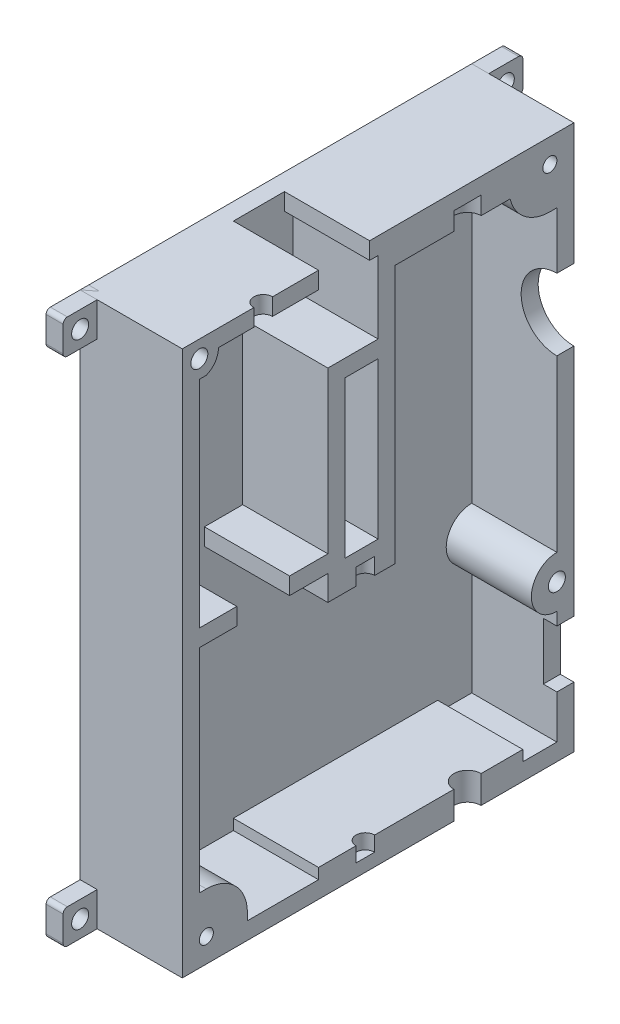
SolidWorks part; units mm, degrees
ref_plane "前视基准面" through (0, 0, 0) normal (0, 0, 1) x (1, 0, 0)
ref_plane "上视基准面" through (0, 0, 0) normal (0, 1, 0) x (1, 0, 0)
ref_plane "右视基准面" through (0, 0, 0) normal (1, 0, 0) x (0, 0, -1)
other "Configuration Table"
sketch "草图1" plane through (0, 0, 0) normal (1, 0, 0) x (0, 0, -1)
  line L1 (-23, 32) -> (23, 32)
  line L2 (-23, 32) -> (-23, -32)
  line L3 (-23, -32) -> (23, -32)
  line L4 (23, 32) -> (23, -32)
  line L5 (-23, 32) -> (23, -32) construction
  line L6 (-23, -32) -> (23, 32) construction
  point P0 (0, 0)
  dimension "D1" = 64
  dimension "D2" = 46
extrude "凸台-拉伸1" add sketch "草图1" along normal blind 12
shell "抽壳1" thickness 2
sketch "草图3" plane through (2, 0, 0) normal (1, 0, 0) x (0, 0, -1)
  line L3 (-6, 23.2) -> (-6, 2.7) construction
  line L10 (-21, 2.7) -> (-6, 2.7) construction
  line L13 (-16.5, 2.7) -> (-16.5, 1.2) construction
  line L14 (-10.5, 1.2) -> (-10.5, 2.7) construction
  line L18 (2.5, -2.55) -> (-5.5, -2.55) construction
  line L19 (-5.9, 21.5) -> (0, 21.5)
  line L20 (-5.9, 21.5) -> (-5.9, 2.6)
  line L21 (-5.9, -2.35) -> (2, -2.35)
  line L22 (2, 17.175) -> (2, -2.35)
  line L25 (8, 24.825) -> (8, -27.175) construction
  line L26 (21, 30) -> (-21, 30) construction
  line L27 (-21, 30) -> (-21, -30) construction
  line L28 (0, 30) -> (2, 30)
  line L29 (0, 30) -> (0, 21.5)
  line L31 (2, 30) -> (2, 17.175)
  line L32 (-3.9, 19.5) -> (0, 19.5)
  line L33 (-3.9, 19.5) -> (-3.9, 1.15)
  line L34 (-3.9, 1.15) -> (0, 1.15)
  line L35 (0, 19.5) -> (0, 1.15)
  line L36 (-21, 2.6) -> (-16.6, 2.6)
  line L37 (-21, 2.6) -> (-21, 0.6)
  line L38 (-21, 0.6) -> (-16.6, 0.6)
  line L39 (-16.6, 2.6) -> (-16.6, 0.6)
  line L41 (-10.4, 2.6) -> (-5.9, 2.6)
  line L42 (-10.4, 2.6) -> (-10.4, 0.6)
  line L43 (-10.4, 0.6) -> (-5.9, 0.6)
  line L48 (-5.9, 0.6) -> (-5.9, -2.35)
  dimension "D2" = 0.2
  dimension "D3" = 6
  dimension "D4" = 8.5
  dimension "D5" = 2
  dimension "D6" = 2
  dimension "D7" = 3.5
  dimension "D8" = 2
  dimension "D9" = 2
  dimension "D10" = 0.1
  dimension "D11" = 0.1
  dimension "D12" = 0.1
  dimension "D13" = 2
  dimension "D14" = 2
  dimension "D15" = 0.1
extrude "机位凸台-拉伸6" add sketch "草图3" along normal up to surface (10 mm away) up to face at (12, 0, 0)
sketch "草图9" plane through (2, 0, 0) normal (1, 0, 0) x (0, 0, -1)
  line L0 (-21, -30) -> (21, -30) construction
  line L1 (-7, -28.75) -> (17, -28.75)
  line L2 (-7, -28.75) -> (-7, -30)
  line L3 (-7, -30) -> (17, -30)
  line L4 (17, -28.75) -> (17, -30)
  line L5 (0.2682, -28.55) -> (1.3325, -28.55) construction
  line L6 (21, -30) -> (21, 30) construction
  dimension "D1" = 0.2
  dimension "D2" = 24
  dimension "D3" = 4
extrude "杆位凸台-拉伸9" add sketch "草图9" along normal up to surface (10 mm away) up to face at (12, 6.1722, 6.4222)
sketch "草图16" plane through (2, 0, 0) normal (1, 0, 0) x (0, 0, -1)
  line L0 (2, 28) -> (21, 28)
  line L1 (2, -2.35) -> (2, 30) construction
  line L2 (21, -30) -> (21, 30) construction
  line L3 (21, 30) -> (2, 30) construction
  line L4 (21, 30) -> (2, 30)
  line L5 (21, 30) -> (21, 28)
  line L6 (2, 28) -> (2, 30)
  dimension "D1" = 2
extrude "凸台-拉伸9" add sketch "草图16" along normal up to surface (10 mm away) up to face at (12, -0.2909, 4.3455)
sketch "草图17" plane through (0, 32, 0) normal (0, 1, 0) x (1, 0, 0)
  circle A1 centre (12, 10.5) radius 1.6
  circle A2 centre (12, 10.5) radius 1.5 construction
  dimension "D1" = 0.1
extrude "后部孔位3切除-拉伸3" cut sketch "草图17" along normal offset from surface (2.1 mm away) 1.9 from surface at -4 up to face at (6, 32, 0) starting at face at (7, 28, -11.5)
sketch "草图4" plane through (0, 32, 0) normal (0, 1, 0) x (1, 0, 0)
  line L1 (12, -1) -> (2, -1)
  line L2 (12, -1) -> (12, -7)
  line L3 (12, -7) -> (2, -7)
  line L4 (2, -1) -> (2, -7)
  line L7 (12, -21) -> (2, -21) construction
  line L8 (2, 0) -> (2, -21) construction
  circle A1 centre (12, -13.5) radius 1.1
  circle A5 centre (12, -13.5) radius 1 construction
  dimension "D1" = 0.1
  dimension "D3" = 14
  dimension "D4" = 6
extrude "后部孔位切除-拉伸1" cut sketch "草图4" against normal up to next
sketch "草图5" plane through (0, -32, 0) normal (0, -1, 0) x (1, 0, 0)
  line L0 (12, -12.1) -> (12, -8.9)
  line L1 (12, 23) -> (12, -23) construction
  arc A3 (12, -8.9) -> (12, -12.1) centre (12, -10.5) ccw
  circle A4 centre (12, -10.5) radius 1.6 construction
extrude "前部切除3-拉伸2" cut sketch "草图5" against normal up to next
sketch "草图11" plane through (0, -32, 0) normal (0, -1, 0) x (1, 0, 0)
  circle A0 centre (12, 1.5) radius 1.1
  circle A1 centre (12, 1.5) radius 1 construction
  dimension "D1" = 0.1
extrude "切除-拉伸2" cut sketch "草图11" against normal up to next from surface
sketch "草图6" plane through (2, 0, 0) normal (1, 0, 0) x (0, 0, -1)
  line L0 (21, -30) -> (21, 28) construction
  line L1 (-23, -32) -> (8.9, -32) construction
  line L2 (-20.175, -24.35) -> (-23, -24.35)
  line L3 (23, -32) -> (23, 32) construction
  line L4 (-23, -24.35) -> (-23, -32)
  line L5 (-21, -30) -> (-7, -30) construction
  line L6 (-23, -32) -> (-15.35, -32)
  line L7 (-21, 0.6) -> (-21, -30) construction
  line L9 (17, -30) -> (21, -30) construction
  line L11 (-23, 28.9692) -> (-23, 31.0308)
  line L12 (-22.0308, 32) -> (-19.9692, 32)
  line L14 (-23, -32) -> (8.9, -32) construction
  line L15 (-23, 32) -> (-23, -32) construction
  line L16 (-14.6, 32) -> (-23, 32) construction
  line L17 (-15.35, -29.175) -> (-15.35, -32)
  line L18 (15.35, 32) -> (23, 32)
  line L19 (23, 32) -> (23, 24.35)
  line L20 (20.175, 24.35) -> (23, 24.35)
  line L21 (15.35, 29.175) -> (15.35, 32)
  line L22 (23, 32) -> (-1, 32) construction
  line L23 (-20.1922, 27.9) -> (-23, 27.9)
  line L24 (-23, 27.9) -> (-23, 28.9692)
  line L25 (23, -11.4639) -> (23, -15.9361)
  circle A0 centre (-20.175, -29.175) radius 0.825
  circle A1 centre (20.175, 29.175) radius 0.825
  circle A2 centre (21, -13.7) radius 1
  circle A3 centre (-21, 30) radius 1
  arc A5 (23, -11.4639) -> (23, -15.9361) centre (21, -13.7) ccw
  arc A7 (-20.1922, 27.9) -> (-19.9692, 32) centre (-21, 30) ccw
  arc A8 (-22.0308, 32) -> (-23, 31.0308) centre (-21, 30) ccw
  arc A10 (-15.35, -29.175) -> (-20.175, -24.35) centre (-20.175, -29.175) ccw
  arc A11 (15.35, 29.175) -> (20.175, 24.35) centre (20.175, 29.175) ccw
  dimension "D1" = 1.65
  dimension "D2" = 1.65
  dimension "D3" = 2
  dimension "D4" = 2
  dimension "D6" = 4
  dimension "D7" = 4
  dimension "D8" = 1.25
  dimension "D9" = 2.825
  dimension "D10" = 2
  dimension "D5" = 16.3
  dimension "D11" = 2.1
extrude "螺丝孔凸台-拉伸7" add sketch "草图6" along normal up to surface (10 mm away) up to face at (12, -9.4222, 10.8111)
sketch "草图7" plane through (12, 0, 0) normal (1, 0, 0) x (0, 0, -1)
  line L0 (21, -14.7) -> (21, -12.7) construction
  circle A1 centre (21, -13.7) radius 1
  circle A3 centre (-21, 30) radius 1
  circle A4 centre (20.175, 29.175) radius 0.825
  arc A5 (21, -12.7) -> (21, -14.7) centre (21, -13.7) ccw construction
  arc A7 (-21, 29) -> (-20, 30) centre (-21, 30) ccw construction
  arc A8 (15.4953, 28) -> (20.175, 24.35) centre (20.175, 29.175) ccw construction
  dimension "D1" = 1.65
extrude "螺丝孔切除-拉伸3" cut sketch "草图7" against normal up to surface (10 mm away) up to face at (2, 3.2227, 3.6014)
sketch "草图12" plane through (0, -2.35, 0) normal (0, -1, 0) x (1, 0, 0)
  line L0 (12, 2.6) -> (12, 0.4)
  arc A0 (12, 2.6) -> (12, 0.4) centre (12, 1.5) ccw construction
  arc A1 (12, 2.6) -> (12, 0.4) centre (12, 1.5) ccw
extrude "2mm切孔切除-拉伸3" cut sketch "草图12" against normal offset from surface (1.95 mm away) 0.1
sketch "草图14" plane through (0, 0, -23) normal (0, 0, -1) x (-1, 0, 0)
  line L0 (-10.5, -20.2) -> (-10.5, -18.4) construction
  line L1 (-13.6, -18.2) -> (-10.4, -18.2)
  line L2 (-13.6, -18.2) -> (-13.6, -24.9)
  line L3 (-13.6, -24.9) -> (-10.4, -24.9)
  line L4 (-10.4, -18.2) -> (-10.4, -24.9)
  line L5 (-12, -32) -> (0, -32) construction
  dimension "D1" = 0.1
  dimension "D2" = 7.1
  dimension "D3" = 6.7
  dimension "D4" = 3.2
extrude "拨杆切除-拉伸4" cut sketch "草图14" against normal up to next
sketch "草图19" plane through (0, 0, -23) normal (0, 0, -1) x (-1, 0, 0)
  circle A0 centre (-12, 13.49) radius 4.2
  circle A1 centre (-12, 13.49) radius 4 construction
  dimension "D1" = 0.2
extrude "竖直传动孔切除-拉伸3" cut sketch "草图19" against normal up to next
sketch "草图20" plane through (0, 0, 0) normal (-1, 0, 0) x (0, 0, 1)
  line L5 (-22, 32) -> (-27, 32)
  line L6 (-22, 32) -> (-22, 28)
  line L7 (-22, 28) -> (-27, 28)
  line L8 (-27, 32) -> (-27, 28)
  line L18 (0, 0) -> (0, -20.7101) construction
  line L19 (0, 0) -> (-28.6873, 0) construction
  line L20 (27, 32) -> (27, 28)
  line L21 (22, 28) -> (27, 28)
  line L22 (22, 32) -> (22, 28)
  line L23 (22, 32) -> (27, 32)
  line L24 (22, -32) -> (27, -32)
  line L25 (22, -32) -> (22, -28)
  line L26 (22, -28) -> (27, -28)
  line L27 (27, -32) -> (27, -28)
  line L28 (-27, -32) -> (-27, -28)
  line L29 (-22, -28) -> (-27, -28)
  line L30 (-22, -32) -> (-22, -28)
  line L31 (-22, -32) -> (-27, -32)
  line L32 (-23, -32) -> (-23, 32) construction
  circle A0 centre (-25, 30) radius 1
  circle A1 centre (25, 30) radius 1
  circle A2 centre (25, -30) radius 1
  circle A3 centre (-25, -30) radius 1
  dimension "D1" = 2
  dimension "D2" = 2
  dimension "D3" = 3
  dimension "D4" = 5
  dimension "D5" = 4
  dimension "D6" = 1
extrude "固定位凸台-拉伸10" add sketch "草图20" against normal blind 2 separate body
fillet "圆角1" radius 0.5 2 edges at (1, -32, -27) (1, -28, -27)
fillet "圆角2" radius 0.5 2 edges at (1, -28, 27) (1, -32, 27)
fillet "圆角3" radius 0.5 2 edges at (1, 32, 27) (1, 28, 27)
fillet "圆角4" radius 0.5 2 edges at (1, 32, -27) (1, 28, -27)
